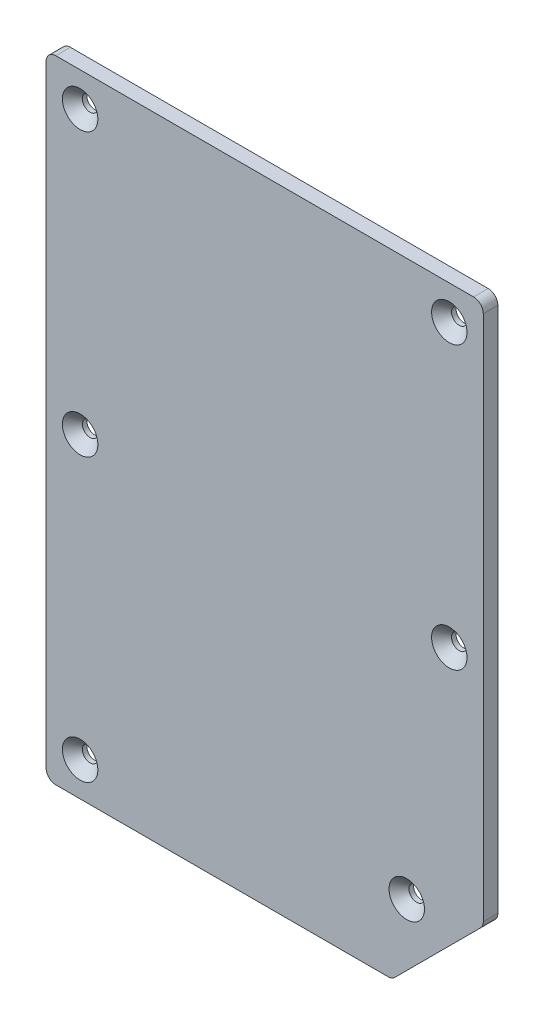
SolidWorks part; units mm, degrees
ref_plane "Front Plane" through (0, 0, 0) normal (0, 0, 1) x (1, 0, 0)
ref_plane "Top Plane" through (0, 0, 0) normal (0, 1, 0) x (1, 0, 0)
ref_plane "Right Plane" through (0, 0, 0) normal (1, 0, 0) x (0, 0, -1)
sketch "Sketch1" plane through (0, 0, 0) normal (0, 0, 1) x (1, 0, 0)
  line B0 (-43, 70) -> (43, 70)
  line B1 (-45, 68) -> (-45, -58)
  line B2 (-43, -60) -> (25.3848, -60)
  line B3 (45, 68) -> (45, -40.3848)
  line B4 (44.4142, -41.799) -> (26.799, -59.4142)
  arc B5 (-43, -60) -> (-45, -58) centre (-43, -58) cw
  arc B6 (45, 68) -> (43, 70) centre (43, 68) ccw
  arc B7 (-43, 70) -> (-45, 68) centre (-43, 68) ccw
  arc B8 (45, -40.3848) -> (44.4142, -41.799) centre (43, -40.3848) cw
  arc B9 (26.799, -59.4142) -> (25.3848, -60) centre (25.3848, -58) cw
sketch_block_instance "Block-B01_block_lid-1"
sketch_block "Block-B01_block_lid"
extrude "Boss-Extrude1" add sketch "Sketch1" along normal blind 3
sketch "Sketch5" plane through (0, 0, 3) normal (0, 0, 1) x (1, 0, 0)
  point P0 (-38, 63)
  point P1 (38, 63)
  point P3 (38, 5)
  point P5 (29.2426, -44.2426)
  point P7 (-38, -53)
  point P9 (-38, 5)
  point P11 (-38, 63)
hole_wizard "CSK for M3 Countersunk Flat Head Screw1" positions "3DSketch3" profile "Sketch6" countersink size "M3" standard "ISO"
sketch3d "3DSketch3"
  point P0 (-38, -53, 3)
  point P3 (29.2426, -44.2426, 3)
  point P6 (38, 5, 3)
  point P9 (-38, 5, 3)
  point P12 (-38, 63, 3)
  point P15 (38, 63, 3)
sketch "Sketch6" plane through (-38, -53, 3) normal (1, 0, 0) x (0, -1, 0)
  line L0 (0, 0) -> (0, 5.9614)
  line L1 (0, 5.9614) -> (1.6, 5)
  line L2 (1.6, 5) -> (1.6, 2.05)
  line L3 (1.6, 2.05) -> (3.65, 0)
  line L5 (3.65, 0) -> (0, 0)
  line L6 (-1.6, 2.05) -> (-3.65, 0) construction
  line L10 (0, 5.9614) -> (-1.6, 5) construction
  line L11 (0, -6.35) -> (0, 107.95) construction
  dimension "Hole Dia." = 3.2
  dimension "Hole Depth" = 5
  dimension "Near C'Sink Dia." = 7.3
  dimension "Near C'Sink Angle" = 90
  dimension "Drill Angle" = 118
